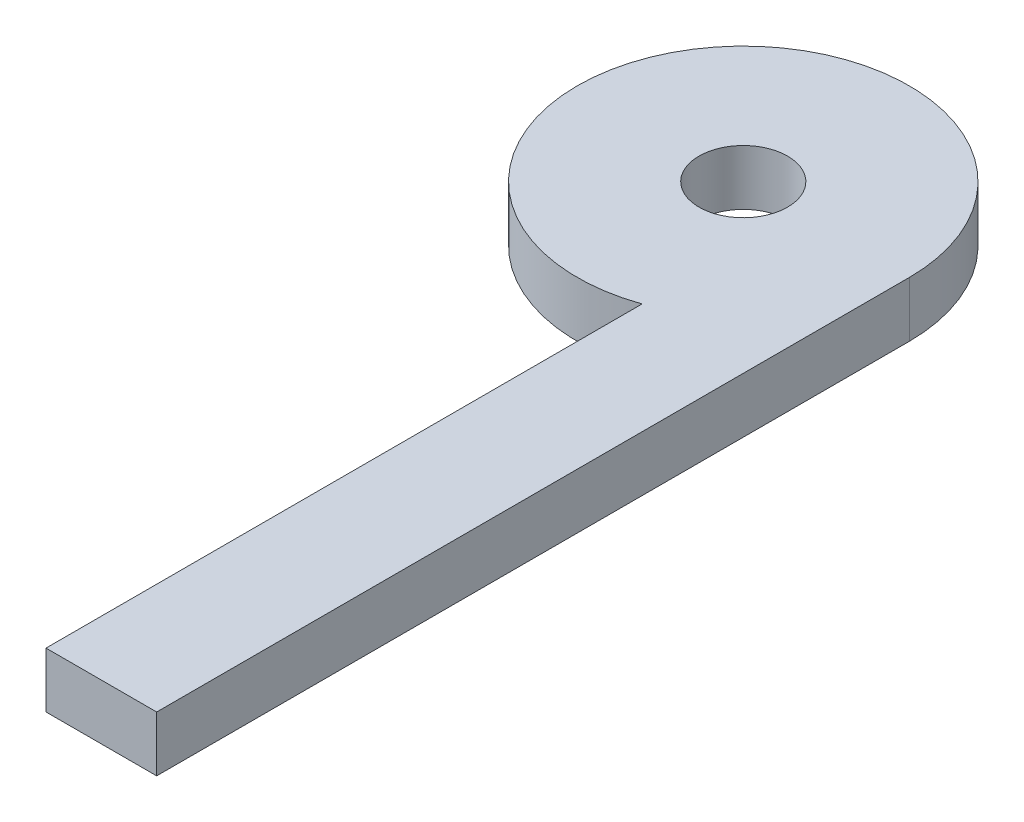
SolidWorks part; units mm, degrees
ref_plane "Front Plane" through (0, 0, 0) normal (0, 0, 1) x (1, 0, 0)
ref_plane "Top Plane" through (0, 0, 0) normal (0, 1, 0) x (1, 0, 0)
ref_plane "Right Plane" through (0, 0, 0) normal (1, 0, 0) x (0, 0, -1)
sketch "Sketch1" plane through (0, 0, 0) normal (0, 1, 0) x (1, 0, 0)
  circle A0 centre (0, 0) radius 19.05
  dimension "D1" = 38.1
extrude "Boss-Extrude1" add sketch "Sketch1" along normal blind 6.35
sketch "Sketch2" plane through (0, 0, 0) normal (0, -1, 0) x (1, 0, 0)
  line L1 (19.05, 0) -> (6.35, 0)
  line L2 (19.05, 0) -> (19.05, 86.36)
  line L3 (19.05, 86.36) -> (6.35, 86.36)
  line L4 (6.35, 0) -> (6.35, 86.36)
  circle A0 centre (0, 0) radius 19.05 construction
  dimension "D1" = 12.7
  dimension "D2" = 86.36
extrude "Boss-Extrude2" add sketch "Sketch2" against normal blind 6.35
sketch "Sketch3" plane through (0, 0, 0) normal (0, -1, 0) x (1, 0, 0)
  circle A0 centre (0, 0) radius 5.08
  dimension "D1" = 10.16
extrude "Cut-Extrude1" cut sketch "Sketch3" against normal blind 6.35
